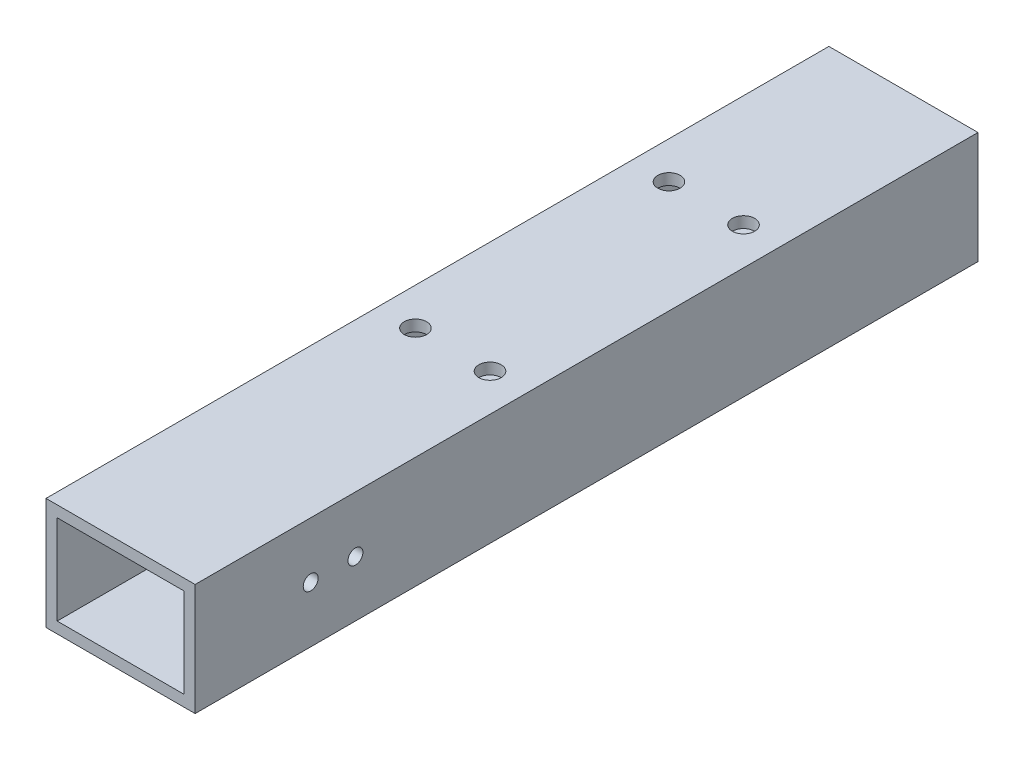
SolidWorks part; units mm, degrees
material "AISI 1015 钢，冷拔 (SS)"
ref_plane "前视基准面" through (0, 0, 0) normal (0, 0, 1) x (1, 0, 0)
ref_plane "上视基准面" through (0, 0, 0) normal (0, 1, 0) x (1, 0, 0)
ref_plane "右视基准面" through (0, 0, 0) normal (1, 0, 0) x (0, 0, -1)
other "Configuration Table"
sketch "草图1" plane through (0, 0, 0) normal (0, 0, 1) x (1, 0, 0)
  line L1 (0, 0) -> (40, 0)
  line L2 (0, 0) -> (0, 30)
  line L3 (0, 30) -> (40, 30)
  line L4 (40, 0) -> (40, 30)
  line L5 (3, 3) -> (37, 3)
  line L6 (3, 3) -> (3, 27)
  line L7 (3, 27) -> (37, 27)
  line L8 (37, 3) -> (37, 27)
  dimension "D1" = 40
  dimension "D2" = 30
  dimension "D3" = 3
  dimension "D4" = 3
  dimension "D5" = 3
  dimension "D6" = 3
extrude "凸台-拉伸1" add sketch "草图1" along normal blind 210
sketch "草图2" plane through (0, 0, 0) normal (1, 0, 0) x (0, 0, -1)
  line L0 (-105, 83.174) -> (-105, -57.7734) construction
  line L1 (-210, 30) -> (0, 30) construction
  line L2 (-234.5233, 15) -> (4.3455, 15) construction
  line L3 (0, 0) -> (0, 30) construction
  circle A0 centre (-167, 15) radius 2
  circle A1 centre (-179, 15) radius 2
  point P2 (-105, 30)
  point P7 (0, 15)
  dimension "D1" = 4
  dimension "D2" = 12
  dimension "D3" = 62
extrude "切除-拉伸1" cut sketch "草图2" along normal through all
sketch "草图3" plane through (0, 0, 0) normal (0, 1, 0) x (1, 0, 0)
  line L0 (20, 7.4176) -> (20, -220.6816) construction
  line L1 (-71.6968, -86.9) -> (105.9098, -86.9) construction
  circle A0 centre (10, -52.9) radius 3
  circle A1 centre (30, -52.9) radius 3
  circle A2 centre (30, -120.9) radius 3
  circle A3 centre (10, -120.9) radius 3
  dimension "D1" = 6
  dimension "D2" = 20
  dimension "D3" = 20
  dimension "D4" = 52.9
  dimension "D5" = 68
extrude "切除-拉伸2" cut sketch "草图3" along normal through all
